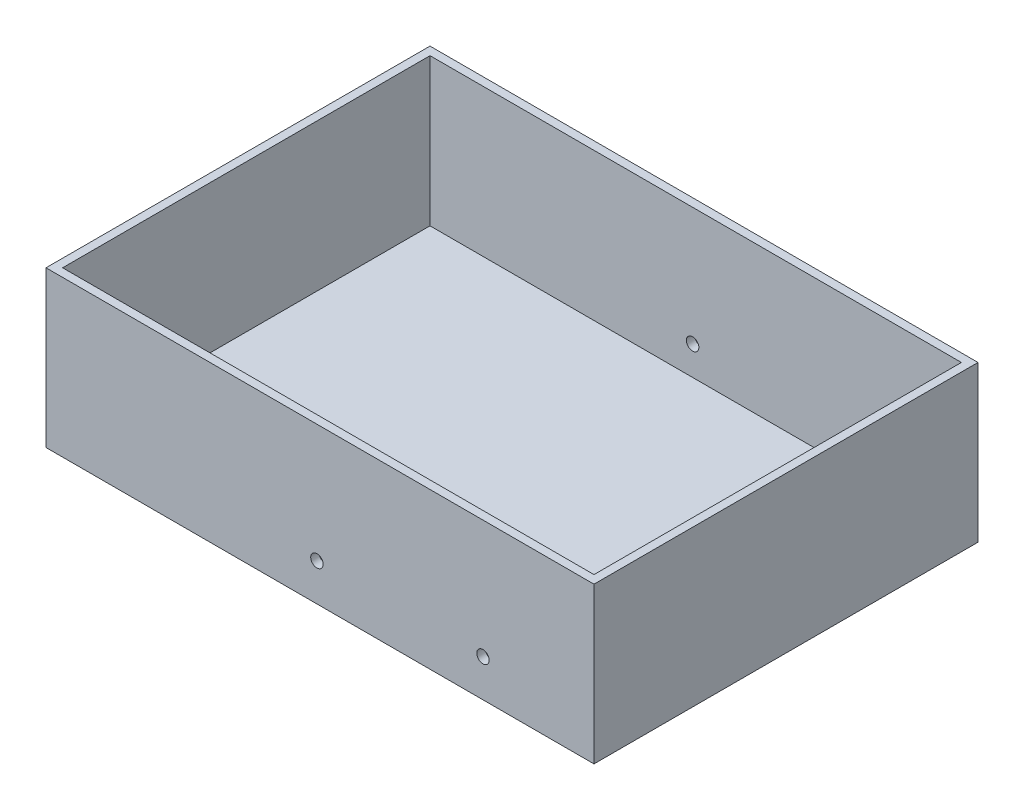
SolidWorks part; units mm, degrees
ref_plane "Front Plane" through (0, 0, 0) normal (0, 0, 1) x (1, 0, 0)
ref_plane "Top Plane" through (0, 0, 0) normal (0, 1, 0) x (1, 0, 0)
ref_plane "Right Plane" through (0, 0, 0) normal (1, 0, 0) x (0, 0, -1)
sketch "Sketch1" plane through (0, 0, 0) normal (0, 1, 0) x (1, 0, 0)
  line L0 (-126.5159, 94.9702) -> (129.4841, 94.9702)
  line L1 (-130.5159, 98.9702) -> (133.4841, 98.9702)
  line L2 (-130.5159, 98.9702) -> (-130.5159, -86.0298)
  line L3 (-130.5159, -86.0298) -> (133.4841, -86.0298)
  line L4 (133.4841, 98.9702) -> (133.4841, -86.0298)
  line L5 (129.4841, 94.9702) -> (129.4841, -82.0298)
  line L6 (-126.5159, -82.0298) -> (129.4841, -82.0298)
  line L7 (-126.5159, 94.9702) -> (-126.5159, -82.0298)
  point P8 (0, 0)
  dimension "D1" = 4
extrude "Boss-Extrude4" add sketch "Sketch1" along normal blind 75
sketch "Sketch6" plane through (0, 0, -94.9702) normal (0, 0, 1) x (1, 0, 0)
  line L0 (129.4841, 75) -> (129.4841, 0) construction
  line L1 (-126.5159, 0) -> (129.4841, 0)
  line L2 (-126.5159, 0) -> (-126.5159, 4)
  line L3 (-126.5159, 4) -> (129.4841, 4)
  line L4 (129.4841, 0) -> (129.4841, 4)
extrude "Boss-Extrude5" add sketch "Sketch6" along normal blind 177 contours L3 L4 L1 L2
sketch "Sketch7" plane through (0, 0, 86.0298) normal (0, 0, 1) x (1, 0, 0)
  circle A0 centre (0, 18) radius 3
  circle A1 centre (80, 18) radius 3
extrude "Cut-Extrude1" cut sketch "Sketch7" against normal blind 185
